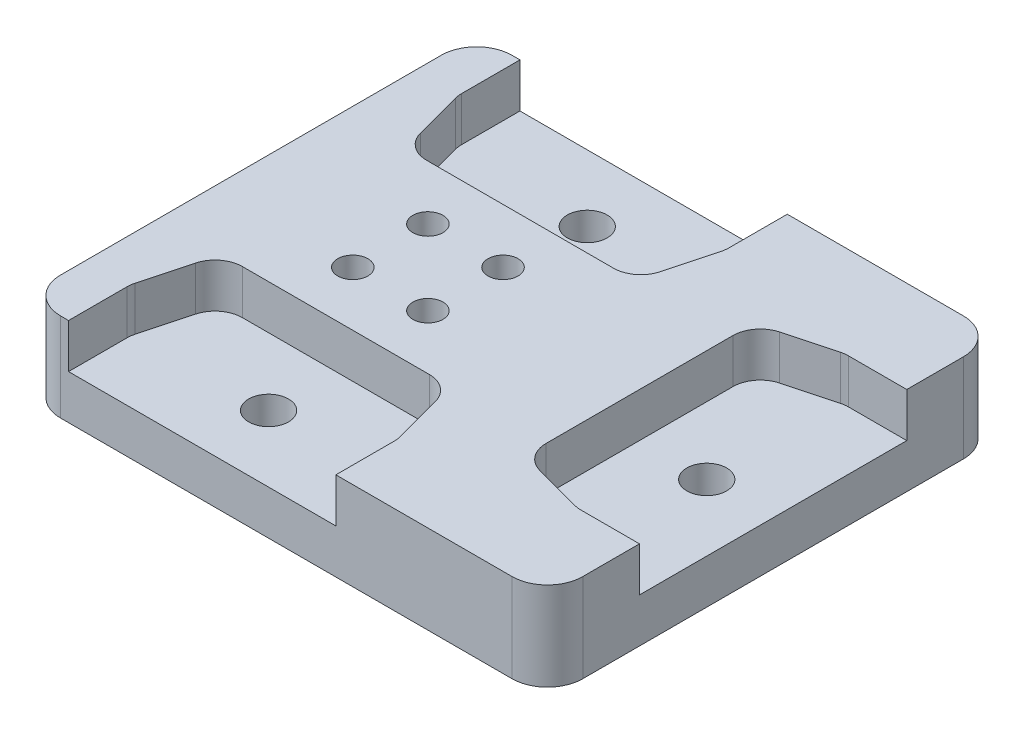
SolidWorks part; units mm, degrees
material "3.1355 (EN-AW 2024)"
ref_plane "Front" through (0, 0, 0) normal (0, 0, 1) x (1, 0, 0)
ref_plane "Top" through (0, 0, 0) normal (0, 1, 0) x (1, 0, 0)
ref_plane "Right" through (0, 0, 0) normal (1, 0, 0) x (0, 0, -1)
sketch "Эскиз1" plane through (0, 0, 0) normal (0, 1, 0) x (1, 0, 0)
  line L1 (0, 0) -> (59, 0)
  line L2 (0, 0) -> (0, 51)
  line L3 (0, 51) -> (59, 51)
  line L4 (59, 0) -> (59, 51)
  dimension "D1" = 51
  dimension "D2" = 59
extrude "Бобышка-Вытянуть1" add sketch "Эскиз1" along normal blind 10
extrude "Вырез-Вытянуть1" cut sketch "Эскиз3" against normal blind 5
sketch "Эскиз3" plane through (28.5214, 10, -17.6817) normal (0, 1, 0) x (1, 0, 0)
  line L5 (-23.5214, -11.0767) -> (-23.5214, -17.6817) construction
  line L6 (-21.9736, -4.9053) -> (-23.4191, -10.3002) construction
  line L7 (2.0331, -2.6817) -> (-19.0758, -2.6817) construction
  line L8 (6.3764, -10.3002) -> (4.9309, -4.9053) construction
  line L9 (6.4786, -17.6817) -> (6.4786, -11.0767) construction
  line L10 (-23.5214, -17.6817) -> (6.4786, -17.6817) construction
  line L11 (-23.6214, -11.0767) -> (-23.6214, -17.7817)
  line L12 (-23.6214, -17.7817) -> (6.5786, -17.7817)
  line L13 (6.5786, -17.7817) -> (6.5786, -11.0767)
  line L14 (6.473, -10.2743) -> (5.0274, -4.8794)
  line L15 (2.0331, -2.5817) -> (-19.0758, -2.5817)
  line L16 (-22.0701, -4.8794) -> (-23.5157, -10.2743)
  arc A4 (-23.4191, -10.3002) -> (-23.5214, -11.0767) centre (-20.5214, -11.0767) ccw construction
  arc A5 (-19.0758, -2.6817) -> (-21.9736, -4.9053) centre (-19.0758, -5.6817) ccw construction
  arc A6 (4.9309, -4.9053) -> (2.0331, -2.6817) centre (2.0331, -5.6817) ccw construction
  arc A7 (6.4786, -11.0767) -> (6.3764, -10.3002) centre (3.4786, -11.0767) ccw construction
  arc A8 (6.5786, -11.0767) -> (6.473, -10.2743) centre (3.4786, -11.0767) ccw
  arc A9 (5.0274, -4.8794) -> (2.0331, -2.5817) centre (2.0331, -5.6817) ccw
  arc A10 (-19.0758, -2.5817) -> (-22.0701, -4.8794) centre (-19.0758, -5.6817) ccw
  arc A11 (-23.5157, -10.2743) -> (-23.6214, -11.0767) centre (-20.5214, -11.0767) ccw
sketch "Эскиз4" plane through (0, 10, 0) normal (0, 1, 0) x (1, 0, 0)
  line L0 (0, 25.5) -> (59, 25.5) construction
  line L1 (0, 51) -> (0, 0) construction
  line L2 (59, 0) -> (59, 51) construction
  line L3 (-1.5512, 38.1977) -> (-0.1056, 43.5926)
  line L4 (-25.6544, 35.9) -> (-4.5456, 35.9)
  line L5 (-30.0944, 43.5926) -> (-28.6488, 38.1977)
  line L6 (-30.2, 51) -> (-30.2, 44.395)
  line L7 (0, 44.395) -> (0, 51)
  line L8 (0, 51) -> (-30.2, 51)
  arc A0 (-1.5512, 38.1977) -> (-4.5456, 35.9) centre (-4.5456, 39) cw
  arc A1 (-25.6544, 35.9) -> (-28.6488, 38.1977) centre (-25.6544, 39) cw
  arc A2 (-30.0944, 43.5926) -> (-30.2, 44.395) centre (-27.1, 44.395) cw
  arc A3 (0, 44.395) -> (-0.1056, 43.5926) centre (-3.1, 44.395) cw
  point P6 (59, 25.5)
  line B0 (46.1977, 11.9512) -> (51.5926, 10.5056)
  line B1 (43.9, 36.0544) -> (43.9, 14.9456)
  line B2 (51.5926, 40.4944) -> (46.1977, 39.0488)
  line B3 (59, 40.6) -> (52.395, 40.6)
  line B4 (52.395, 10.4) -> (59, 10.4)
  line B5 (59, 40.6) -> (59, 10.4)
  arc B6 (46.1977, 11.9512) -> (43.9, 14.9456) centre (47, 14.9456) cw
  arc B7 (43.9, 36.0544) -> (46.1977, 39.0488) centre (47, 36.0544) cw
  arc B8 (51.5926, 40.4944) -> (52.395, 40.6) centre (52.395, 37.5) cw
  arc B9 (52.395, 10.4) -> (51.5926, 10.5056) centre (52.395, 13.5) cw
sketch_block_instance "Блок1-2"
sketch_block "Блок1"
extrude "Вырез-Вытянуть2" cut sketch "Эскиз4" against normal up to surface (5 mm away) up to face at (20, 5, -8.4853)
sketch "Эскиз12" plane through (0, 10, 0) normal (0, 1, 0) x (1, 0, 0)
  line L0 (35.1, 6.605) -> (35.1, 0) construction
  line L1 (34.9944, 7.4074) -> (33.5488, 12.8023) construction
  line L2 (30.5544, 15.1) -> (9.4456, 15.1) construction
  line L3 (6.4512, 12.8023) -> (5.0056, 7.4074) construction
  line L4 (4.9, 6.605) -> (4.9, 0) construction
  line L5 (35.1, 6.605) -> (35.1, 0) construction
  line L6 (34.9944, 7.4074) -> (33.5488, 12.8023) construction
  line L7 (30.5544, 15.1) -> (9.4456, 15.1) construction
  line L8 (6.4512, 12.8023) -> (5.0056, 7.4074) construction
  line L9 (4.9, 6.605) -> (4.9, 0) construction
  line L10 (0, 25.5) -> (59, 25.5) construction
  line L11 (0, 51) -> (0, 0) construction
  line L12 (59, 40.6) -> (59, 10.4) construction
  line L13 (4.9, 44.395) -> (4.9, 51)
  line L14 (6.4512, 38.1977) -> (5.0056, 43.5926)
  line L15 (30.5544, 35.9) -> (9.4456, 35.9)
  line L16 (34.9944, 43.5926) -> (33.5488, 38.1977)
  line L17 (35.1, 44.395) -> (35.1, 51)
  line L18 (4.9, 51) -> (35.1, 51)
  arc A0 (35.1, 6.605) -> (34.9944, 7.4074) centre (32, 6.605) ccw construction
  arc A1 (33.5488, 12.8023) -> (30.5544, 15.1) centre (30.5544, 12) ccw construction
  arc A2 (9.4456, 15.1) -> (6.4512, 12.8023) centre (9.4456, 12) ccw construction
  arc A3 (5.0056, 7.4074) -> (4.9, 6.605) centre (8, 6.605) ccw construction
  arc A4 (35.1, 6.605) -> (34.9944, 7.4074) centre (32, 6.605) ccw construction
  arc A5 (33.5488, 12.8023) -> (30.5544, 15.1) centre (30.5544, 12) ccw construction
  arc A6 (9.4456, 15.1) -> (6.4512, 12.8023) centre (9.4456, 12) ccw construction
  arc A7 (5.0056, 7.4074) -> (4.9, 6.605) centre (8, 6.605) ccw construction
  arc A8 (5.0056, 43.5926) -> (4.9, 44.395) centre (8, 44.395) cw
  arc A9 (9.4456, 35.9) -> (6.4512, 38.1977) centre (9.4456, 39) cw
  arc A10 (33.5488, 38.1977) -> (30.5544, 35.9) centre (30.5544, 39) cw
  arc A11 (35.1, 44.395) -> (34.9944, 43.5926) centre (32, 44.395) cw
sketch "Эскиз5" plane through (0, 10, 0) normal (0, 1, 0) x (1, 0, 0)
  line L0 (20, 35.9) -> (20, 15.1) construction
  line L2 (30.5544, 15.1) -> (9.4456, 15.1) construction
  line L3 (15.7574, 29.7426) -> (20, 25.5) construction
  line L4 (20, 25.5) -> (14, 25.5) construction
  line L5 (24.2426, 29.7426) -> (20, 25.5) construction
  line L6 (24.2426, 21.2574) -> (20, 25.5) construction
  line L7 (15.7574, 21.2574) -> (20, 25.5) construction
  line L8 (30.5544, 35.9) -> (9.4456, 35.9) construction
  circle A0 centre (20, 25.5) radius 6 construction
  point P16 (20, 25.5)
  dimension "D1" = 12
  dimension "D2" = 45
  dimension "D3" = 4
hole_wizard "Отверстие с зазором M31" positions "Эскиз7" profile "Эскиз6" hole size "M3" standard "Ansi Metric" end condition through all
sketch "Эскиз7" plane through (0, 0, 0) normal (0, -1, 0) x (-1, 0, 0)
  point P0 (-24.2426, 29.7426)
  point P3 (-15.7574, 29.7426)
  point P6 (-15.7574, 21.2574)
  point P9 (-24.2426, 21.2574)
sketch "Эскиз6" plane through (24.2426, 0, -29.7426) normal (1, 0, 0) x (0, 0, -1)
  line L0 (0, 0) -> (0, 10)
  line L1 (0, 10) -> (1.7, 10)
  line L2 (1.7, 10) -> (1.7, 0)
  line L5 (1.7, 0) -> (0, 0)
  line L11 (0, -6.35) -> (0, 107.95) construction
  dimension "Диаметр сквозного отверстия" = 3.4
  dimension "Глубина сквозного отверстия" = 10
sketch "Эскиз8" plane through (0, 10, 0) normal (0, 1, 0) x (1, 0, 0)
  line L0 (20, 25.5) -> (150, 25.5) construction
  line L1 (59, 51) -> (0, 51) construction
  line L2 (59, 0) -> (150, 0)
  line L3 (59, 0) -> (59, 51)
  line L4 (59, 51) -> (150, 51)
  line L5 (150, 0) -> (150, 51)
  dimension "D1" = 130
extrude "Бобышка-Вытянуть2" [suppressed] add sketch "Эскиз8" against normal through all
sketch "Эскиз9" [suppressed] plane through (0, 0, 0) normal (0, -1, 0) x (1, 0, 0)
  line L0 (140, 0) -> (35, 0)
  line L1 (0, 0) -> (150, 0) construction
  line L2 (0, -51) -> (0, 0) construction
  line L3 (150, 0) -> (150, -51) construction
  line L4 (150, -25.5) -> (0, -25.5) construction
  spline S0 degree 3 poles (140, 0) (86.4416, -20.3357) (47.1176, -4.1079) (35, 0) knots 0 0 0 0 1 1 1 1
  dimension "D1" = 35
  dimension "D2" = 10
extrude "Вырез-Вытянуть3" [suppressed] cut sketch "Эскиз9" against normal blind 10
fillet "Скругление1" radius 4 2 edges at (0, 5, -51) (0, 5, 0)
fillet "Скругление2" radius 4 2 edges at (59, 5, -51) (59, 5, 0)
hole_wizard "Отверстие с зазором M41" positions "Эскиз11" profile "Эскиз10" hole size "M4" standard "Ansi Metric"
sketch "Эскиз11" plane through (0, 0, 0) normal (0, -1, 0) x (-1, 0, 0)
  point P0 (-51.5, 25.5)
  point P3 (-20, 43.5)
  point P6 (-20, 7.5)
sketch "Эскиз10" plane through (51.5, 0, -25.5) normal (1, 0, 0) x (0, 0, -1)
  line L0 (0, 0) -> (0, 5)
  line L1 (0, 5) -> (2.25, 5)
  line L2 (2.25, 5) -> (2.25, 0)
  line L5 (2.25, 0) -> (0, 0)
  line L11 (0, -6.35) -> (0, 107.95) construction
  dimension "Диаметр сквозного отверстия" = 4.5
  dimension "Глубина сквозного отверстия" = 5
extrude "Вырез-Вытянуть4" cut sketch "Эскиз12" against normal up to surface (5 mm away) up to face at (20, 5, -5.25)
